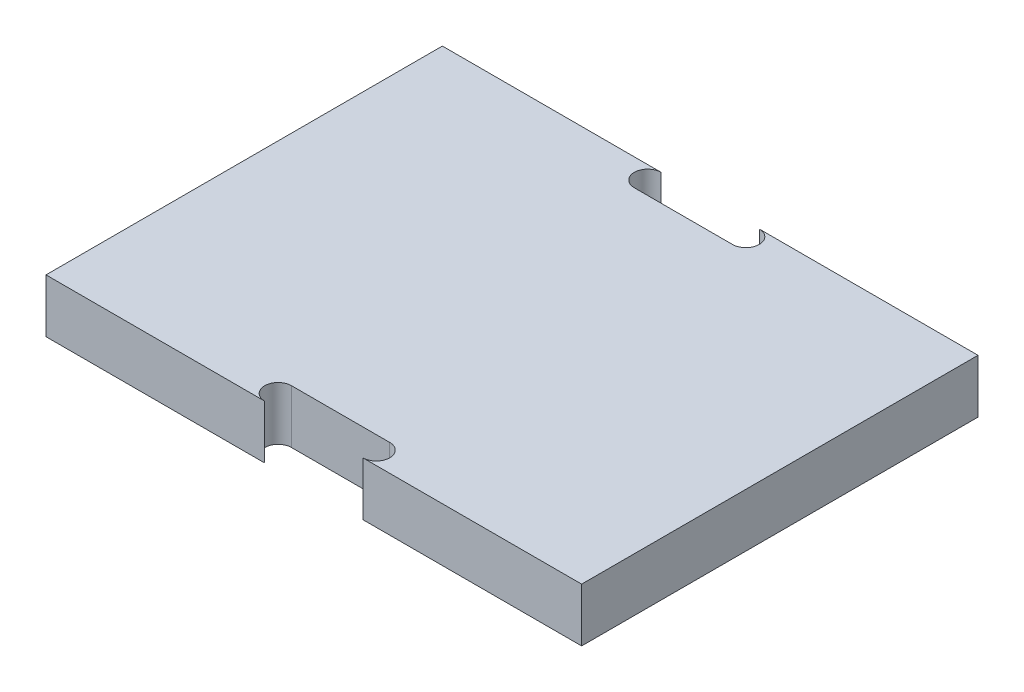
SolidWorks part; units mm, degrees
ref_plane "Front Plane" through (0, 0, 0) normal (0, 0, 1) x (1, 0, 0)
ref_plane "Top Plane" through (0, 0, 0) normal (0, 1, 0) x (1, 0, 0)
ref_plane "Right Plane" through (0, 0, 0) normal (1, 0, 0) x (0, 0, -1)
sketch "Sketch1" plane through (0, 0, 0) normal (0, 1, 0) x (1, 0, 0)
  line L1 (-33, 0) -> (33, 0) construction
  line L3 (-30, 0) -> (-30, 22.2)
  line L4 (30, 0) -> (30, 22.2)
  line L5 (-30, 0) -> (-30, -22.2)
  line L6 (0, -24.42) -> (0, 24.42) construction
  line L7 (0, 19.2) -> (5.5, 19.2)
  line L8 (0, 19.2) -> (-5.5, 19.2)
  line L9 (-30, 22.2) -> (-5.5, 22.2)
  line L10 (30, 22.2) -> (5.5, 22.2)
  line L12 (0, 0) -> (-30, 0) construction
  line L13 (30, 0) -> (0, 0) construction
  line L14 (-30, -22.2) -> (-5.5, -22.2)
  line L15 (30, -22.2) -> (30, 0)
  line L16 (30, -22.2) -> (5.5, -22.2)
  line L17 (0, -19.2) -> (-5.5, -19.2)
  line L18 (0, -19.2) -> (5.5, -19.2)
  arc A0 (-5.5, 22.2) -> (-5.5, 19.2) centre (-5.5, 20.7) ccw
  arc A1 (5.5, 22.2) -> (5.5, 19.2) centre (5.5, 20.7) cw
  arc A2 (-5.5, -19.2) -> (-5.5, -22.2) centre (-5.5, -20.7) ccw
  arc A3 (5.5, -19.2) -> (5.5, -22.2) centre (5.5, -20.7) cw
  point P0 (0, 0)
  point P20 (0, 0)
  point P21 (0, -19.2)
  dimension "D1" = 22.2
  dimension "D5" = 24.5
  dimension "D2" = 22.2
  dimension "D3" = 22.2
  dimension "D4" = 24.5
  dimension "D6" = 24.5
  dimension "D7" = 19.2
  dimension "D8" = 19.2
extrude "Boss-Extrude1" add sketch "Sketch1" along normal blind 6
